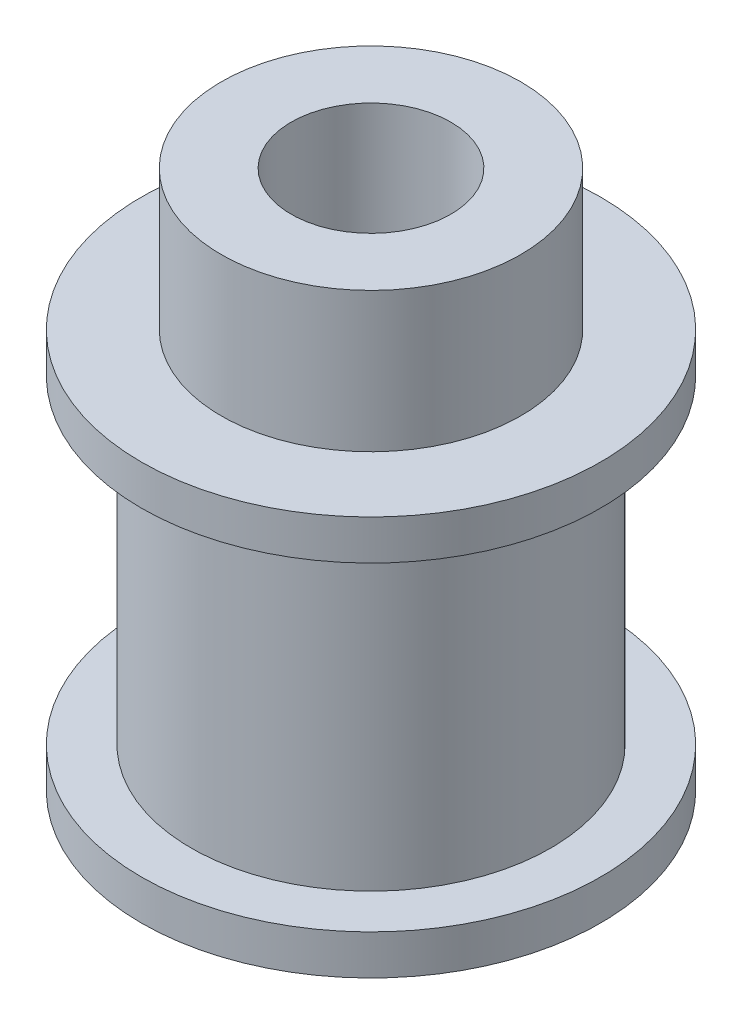
SolidWorks part; units mm, degrees
ref_plane "Alzado" through (0, 0, 0) normal (0, 0, 1) x (1, 0, 0)
ref_plane "Planta" through (0, 0, 0) normal (0, 1, 0) x (1, 0, 0)
ref_plane "Vista lateral" through (0, 0, 0) normal (1, 0, 0) x (0, 0, -1)
sketch "Croquis1" plane through (0, 0, 0) normal (0, 0, 1) x (1, 0, 0)
  line L0 (0, 0) -> (0, 34.7627) construction
  line L1 (-4, 0) -> (-11.5, 0)
  line L2 (-11.5, 0) -> (-11.5, 2)
  line L3 (-11.5, 2) -> (-9, 2)
  line L4 (-9, 2) -> (-9, 18)
  line L5 (-9, 18) -> (-11.5, 18)
  line L6 (-11.5, 18) -> (-11.5, 20)
  line L7 (-11.5, 20) -> (-7.5, 20)
  line L8 (-7.5, 20) -> (-7.5, 27)
  line L9 (-7.5, 27) -> (-4, 27)
  line L10 (-4, 27) -> (-4, 0)
  dimension "D1" = 4
  dimension "D2" = 7.5
  dimension "D3" = 11.5
  dimension "D4" = 9
  dimension "D5" = 2
  dimension "D6" = 2
  dimension "D7" = 16
  dimension "D8" = 7
revolve "Revolución1" add sketch "Croquis1" angle 360 about L0
